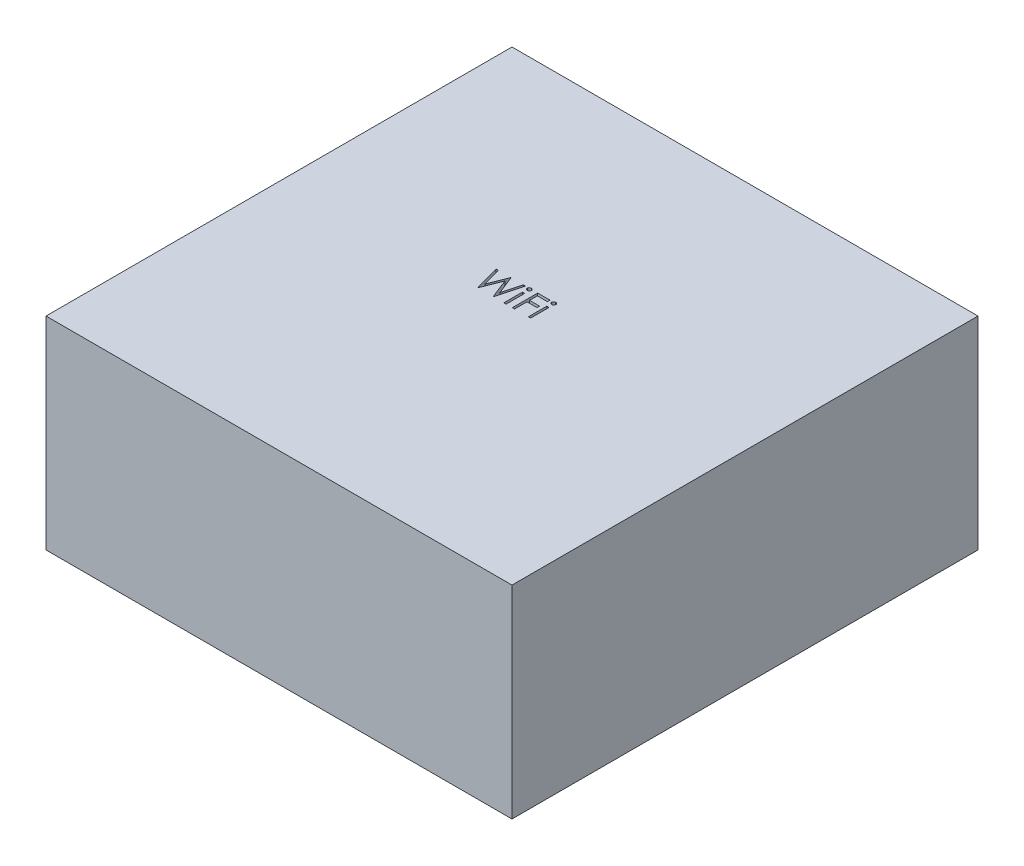
SolidWorks part; units mm, degrees
ref_plane "Front Plane" through (0, 0, 0) normal (0, 0, 1) x (1, 0, 0)
ref_plane "Top Plane" through (0, 0, 0) normal (0, 1, 0) x (1, 0, 0)
ref_plane "Right Plane" through (0, 0, 0) normal (1, 0, 0) x (0, 0, -1)
sketch "Sketch1" plane through (0, 0, 0) normal (0, 1, 0) x (1, 0, 0)
  line L1 (0, 0) -> (58.42, 0)
  line L2 (0, 0) -> (0, 58.42)
  line L3 (0, 58.42) -> (58.42, 58.42)
  line L4 (58.42, 0) -> (58.42, 58.42)
extrude "Boss-Extrude1" add sketch "Sketch1" along normal blind 25.4
sketch "Sketch2" plane through (0, 25.4, 0) normal (0, 1, 0) x (1, 0, 0)
  text T0 "WiFi"
extrude "Cut-Extrude1" cut sketch "Sketch2" against normal blind 7.62
